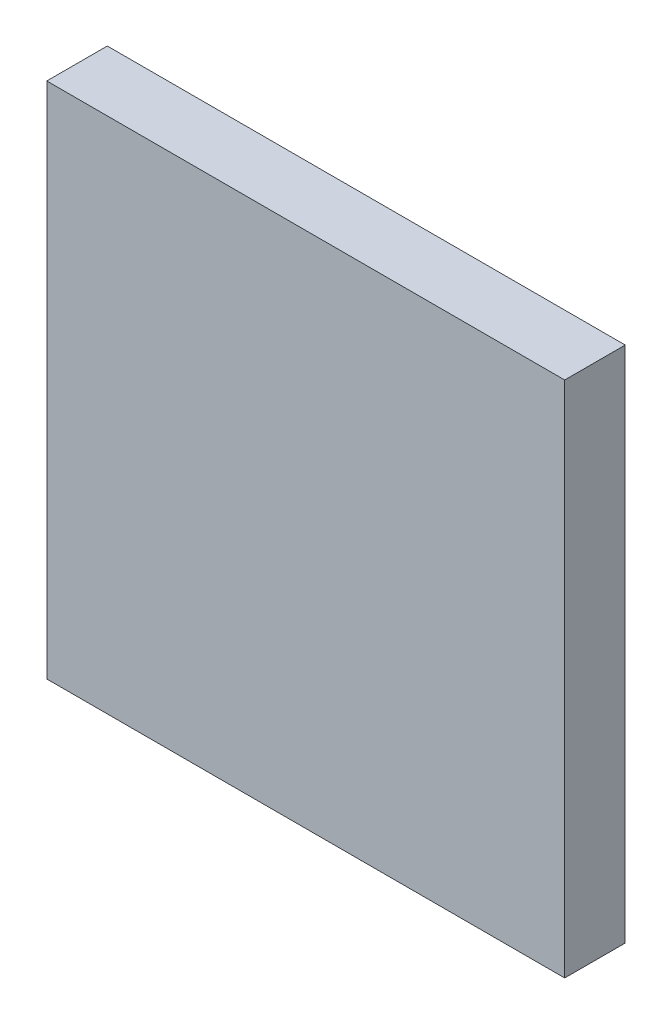
SolidWorks part; units mm, degrees
ref_plane "Přední rovina" through (0, 0, 0) normal (0, 0, 1) x (1, 0, 0)
ref_plane "Horní rovina" through (0, 0, 0) normal (0, 1, 0) x (1, 0, 0)
ref_plane "Pravá rovina" through (0, 0, 0) normal (1, 0, 0) x (0, 0, -1)
sketch "Skica1" plane through (0, 0, 0) normal (0, 0, 1) x (1, 0, 0)
  line L0 (0, 98.8461) -> (0, -124.9525) construction
  line L1 (-6.25, -75.7426) -> (-6.25, -80)
  line L2 (-6.25, -80) -> (-80, -80)
  line L3 (-80, -80) -> (-80, 80)
  line L4 (-80, 80) -> (80, 80)
  line L5 (80, 80) -> (80, -80)
  line L6 (80, -80) -> (6.25, -80)
  line L7 (6.25, -80) -> (6.25, -75.7426)
  arc A0 (-6.25, -75.7426) -> (6.25, -75.7426) centre (0, 0) cw
  dimension "D1" = 76
  dimension "D2" = 6.25
  dimension "D3" = 6.25
  dimension "D4" = 80
  dimension "D5" = 80
  dimension "D6" = 80
  dimension "D7" = 80
extrude "Přidat vysunutím1" add sketch "Skica1" along normal blind 1.7 contours L4 L5 L6 L7 A0 L1 L2 L3
sketch "Skica2" plane through (0, 0, 1.7) normal (0, 0, 1) x (1, 0, 0)
  line L1 (-80, 80) -> (80, 80)
  line L2 (-80, 80) -> (-80, -80)
  line L3 (-80, -80) -> (80, -80)
  line L4 (80, 80) -> (80, -80)
  circle A0 centre (0, 0) radius 76
  dimension "D1" = 152
extrude "Přidat vysunutím2" add sketch "Skica2" along normal blind 15
sketch "Skica4" plane through (0, 0, 16.7) normal (0, 0, 1) x (1, 0, 0)
  line L1 (-80, 80) -> (80, 80)
  line L2 (-80, 80) -> (-80, -80)
  line L3 (-80, -80) -> (80, -80)
  line L4 (80, 80) -> (80, -80)
extrude "Přidat vysunutím3" add sketch "Skica4" along normal blind 2
